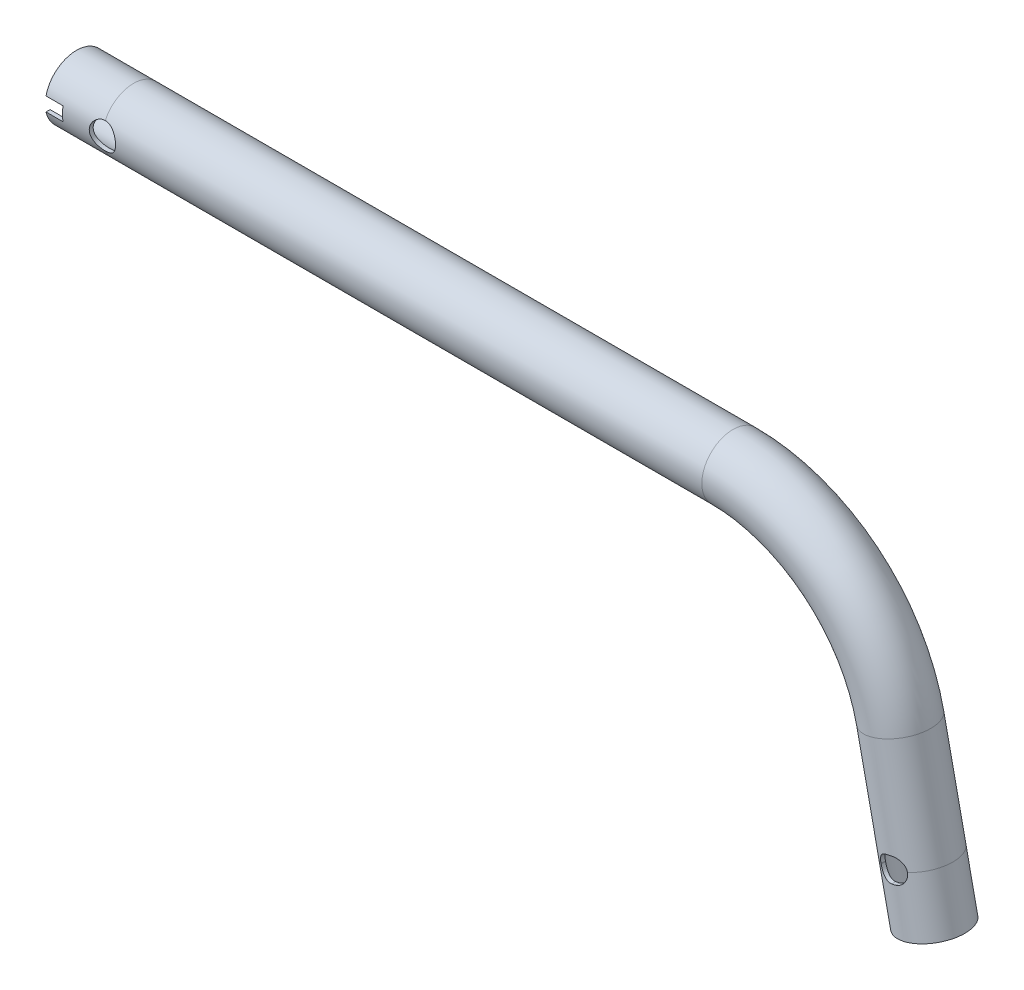
SolidWorks part; units mm, degrees
ref_plane "Front Plane" through (0, 0, 0) normal (0, 0, 1) x (1, 0, 0)
ref_plane "Top Plane" through (0, 0, 0) normal (0, 1, 0) x (1, 0, 0)
ref_plane "Right Plane" through (0, 0, 0) normal (1, 0, 0) x (0, 0, -1)
sketch "Sketch1" plane through (0, 0, 0) normal (0, 0, 1) x (1, 0, 0)
  line L0 (0, 0) -> (182.3746, 0)
  line L1 (233.2383, -41.1886) -> (240, -73)
  line L2 (0, 0) -> (-17.3865, 0)
  line L3 (240, -73) -> (243.6135, -90)
  arc A0 (233.2383, -41.1886) -> (182.3746, 0) centre (182.3746, -52) ccw
  point P10 (240, -73)
  dimension "D2" = 52
  dimension "D1" = 78
  dimension "D3" = 240
  dimension "D4" = 73
  dimension "D5" = 261
  dimension "D6" = 90
ref_plane "Plane1" through (-17.3865, 0, 0) normal (-1, 0, 0) x (0, 0, 1)
sketch "Sketch2" plane through (-17.3865, 0, 0) normal (-1, 0, 0) x (0, 0, 1)
  circle A0 centre (0, 0) radius 9.5
  circle A1 centre (0, 0) radius 8.3
  dimension "D1" = 1.2
sweep "Sweep1" add profiles "Sketch2" path "Sketch1"
sketch "Sketch3" plane through (0, 0, 0) normal (0, 0, 1) x (1, 0, 0)
  line L0 (240, -73) -> (244.0104, -72.1476) construction
  line L1 (230.7076, -74.9752) -> (249.2924, -71.0248) construction
  line L2 (240, -73) -> (239.2619, -69.5276) construction
  line L3 (244.0278, -72.2293) -> (243.993, -72.0658)
  line L4 (239.8418, -69.37) -> (238.668, -69.6195)
  line L5 (235.9722, -73.7707) -> (236.007, -73.9342)
  line L6 (240.1582, -76.63) -> (241.332, -76.3805)
  arc A0 (240.1582, -76.63) -> (236.007, -73.9342) centre (239.4305, -73.2065) cw
  arc A1 (241.332, -76.3805) -> (244.0278, -72.2293) centre (240.6043, -72.957) ccw
  arc A2 (243.993, -72.0658) -> (239.8418, -69.37) centre (240.5695, -72.7935) ccw
  arc A3 (238.668, -69.6195) -> (235.9722, -73.7707) centre (239.3957, -73.043) ccw
  point P8 (244.0104, -72.1476)
  point P14 (244.7555, -75.6528)
  point P17 (243.2653, -68.6423)
  point P20 (235.2445, -70.3472)
  dimension "D6" = 3.5
  dimension "D1" = 4.1
  dimension "D2" = 3.55
  dimension "D3" = 90
  dimension "D4" = 7.1671
  dimension "D5" = 8.2
extrude "Cut-Extrude1" cut sketch "Sketch3" against normal up to next and the other way up to next
sketch "Sketch4" plane through (0, 0, 0) normal (0, 0, 1) x (1, 0, 0)
  line L0 (0, -9.5) -> (0, 9.5) construction
  circle A0 centre (0, 0) radius 4
extrude "Cut-Extrude2" cut sketch "Sketch4" along normal up to next
sketch "Sketch5" plane through (0, 0, 0) normal (0, 0, 1) x (1, 0, 0)
  line L0 (-17.3865, 0) -> (-17.3865, 2.1)
  line L1 (-17.3865, 9.5) -> (-17.3865, -9.5) construction
  line L2 (-17.3865, 2.1) -> (-12.1865, 2.1)
  line L3 (-12.1865, 2.1) -> (-12.1865, -2.1)
  line L4 (-12.1865, -2.1) -> (-17.3865, -2.1)
  line L5 (-17.3865, -2.1) -> (-17.3865, 0)
  dimension "D1" = 5.2
  dimension "D2" = 4.2
extrude "Cut-Extrude3" cut sketch "Sketch5" against normal through all and the other way through all
